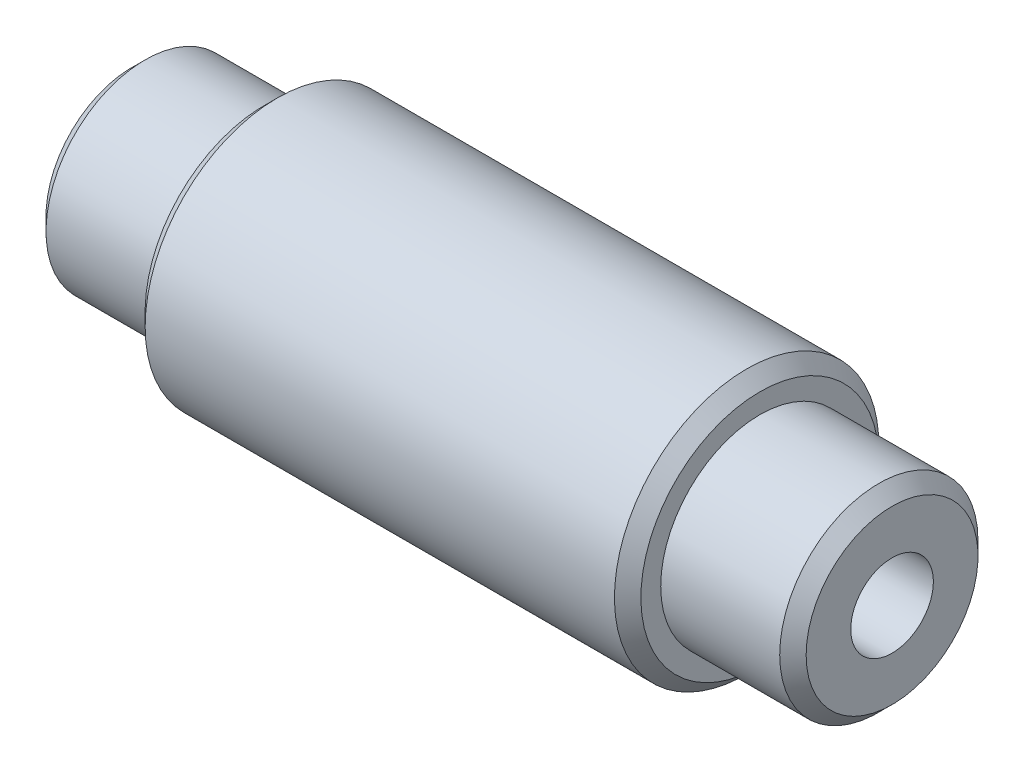
SolidWorks part; units mm, degrees
material "A2017-T4"
ref_plane "Front Plane" through (0, 0, 0) normal (0, 0, 1) x (1, 0, 0)
ref_plane "Top Plane" through (0, 0, 0) normal (0, 1, 0) x (1, 0, 0)
ref_plane "Right Plane" through (0, 0, 0) normal (1, 0, 0) x (0, 0, -1)
sketch "Sketch1" plane through (0, 0, 0) normal (0, 0, 1) x (1, 0, 0)
  line L0 (15, 0) -> (0, 0) construction
  line L3 (0, 0) -> (0, 4)
  line L4 (0, 4) -> (15, 4)
  line L5 (15, 4) -> (15, 0)
  line L8 (0, 0) -> (15, 0)
  dimension "D" = 8
  dimension "L" = 15
revolve "Revolve1" add sketch "Sketch1" angle 360 about L0
chamfer "Chamfer1" distance 0.4 angle 45 2 edges at (0, 4, 0) (15, 4, 0)
ref_plane "Dim. SC" through (6, 0, 0) normal (1, 0, 0) x (0, 0, -1)
ref_plane "Plane1" through (-4, 0, 0) normal (1, 0, 0) x (0, 0, -1)
ref_plane "Plane2" through (19, 0, 0) normal (1, 0, 0) x (0, 0, -1)
sketch "Sketch2" plane through (0, 0, 0) normal (0, 0, 1) x (1, 0, 0)
  line L0 (-4, 0) -> (19, 0) construction
  line L1 (-4, 0) -> (-4, 3)
  line L2 (15, 3) -> (15, 0) construction
  line L3 (0, 0) -> (0, 4) construction
  line L4 (-4, 3) -> (-4, 0) construction
  line L5 (19, 3) -> (19, 0) construction
  line L6 (-4, 3) -> (19, 3)
  line L7 (19, 3) -> (19, 0)
  line L8 (-4, 0) -> (19, 0)
  line L12 (-4, -5.5) -> (-4, 5.5) construction
  line L13 (19, -5.5) -> (19, 5.5) construction
  dimension "P" = 6
  dimension "E" = 4
  dimension "L" = 15
  dimension "F" = 4
  dimension "V" = 6
revolve "Revolve2" add sketch "Sketch2" angle 360 about L0
hole_wizard "Tapped Hole1" positions "Sketch4" profile "Sketch3" tap size "M4x0.7" standard "JIS"
sketch "Sketch4" plane through (-4, 0, 0) normal (1, 0, 0) x (0, 0, -1)
  point P0 (0, 0)
sketch "Sketch3" plane through (-4, 0, 0) normal (0, 1, 0) x (0, 0, 1)
  line L0 (0, 0) -> (0, 9.2511)
  line L1 (0, 9.2511) -> (1.25, 8.5)
  line L2 (1.25, 8.5) -> (1.25, 0)
  line L3 (1.5, 8.5) -> (1.5, 0) construction
  line L5 (1.25, 0) -> (0, 0)
  line L10 (0, 9.2511) -> (-1.25, 8.5) construction
  line L11 (0, 0) -> (0, 9.2511) construction
  dimension "Tap Drill Dia." = 2.5
  dimension "Tap Drill Depth" = 8.5
  dimension "Drill Angle" = 118
  dimension "Pilot hole Tip" = 9.2511
  dimension "M" = 3
cosmetic thread "Hole Thread1" parameters "Mx2"=6, "M"=3
hole_wizard "Tapped Hole2" positions "Sketch6" profile "Sketch5" tap size "M4x0.7" standard "JIS"
sketch "Sketch6" plane through (19, 1.8547, 0.4609) normal (1, 0, 0) x (0, 0, -1)
  point P0 (0.4609, -1.8547)
sketch "Sketch5" plane through (19, 0, 0) normal (0, 1, 0) x (0, 0, -1)
  line L0 (0, 0) -> (0, 9.2511)
  line L1 (0, 9.2511) -> (1.25, 8.5)
  line L2 (1.25, 8.5) -> (1.25, 0)
  line L3 (1.5, 8.5) -> (1.5, 0) construction
  line L5 (1.25, 0) -> (0, 0)
  line L10 (0, 9.2511) -> (-1.25, 8.5) construction
  line L11 (0, 0) -> (0, 9.2511) construction
  dimension "Tap Drill Dia." = 2.5
  dimension "Tap Drill Depth" = 8.5
  dimension "Drill Angle" = 118
  dimension "Pilot hole Tip" = 9.2511
  dimension "N" = 3
cosmetic thread "Hole Thread2" parameters "Nx2"=6, "N"=3
sketch "Sketch7" plane through (-4, 0, 0) normal (1, 0, 0) x (0, 0, -1)
  circle A0 centre (0, 0) radius 1.25
  circle A1 centre (0, 0) radius 1.25
  dimension "D1" = 2.5
  dimension "D2" = 2.5
extrude "Boss-Extrude1" [suppressed] add sketch "Sketch7" along normal blind 6
sketch "Sketch8" plane through (19, 0, 0) normal (1, 0, 0) x (0, 0, -1)
  circle A0 centre (0, 0) radius 1.25
  circle A1 centre (0, 0) radius 1.25
  dimension "D1" = 2.5
  dimension "D2" = 2.5
extrude "Boss-Extrude2" [suppressed] add sketch "Sketch8" against normal blind 6
chamfer "Chamfer2" distance 0.4 angle 45 1 edges at (-4, 0, 3)
chamfer "Chamfer3" distance 0.4 angle 45 1 edges at (19, 0, 3)
ref_plane "Plane3" [suppressed] through (-2, 0, 0) normal (1, 0, 0) x (0, 0, -1)
ref_plane "Plane4" [suppressed] through (27, 0, 0) normal (1, 0, 0) x (0, 0, -1)
sketch "Sketch9" [suppressed] plane through (0, 0, 0) normal (0, 0, 1) x (1, 0, 0)
  line L0 (-2, 0) -> (27, 0) construction
  line L1 (-2, 0) -> (-2, 4) construction
  line L2 (0, 4.6) -> (0, -4.6) construction
  line L4 (-2, 4) -> (-2, 0)
  line L5 (27, 4) -> (27, 0)
  line L6 (-2, 4) -> (27, 4)
  line L7 (27, 4) -> (27, 0) construction
  line L8 (-2, 0) -> (27, 0)
  line L9 (-2, -5.5) -> (-2, 5.5) construction
  line L10 (27, -5.5) -> (27, 5.5) construction
  line L11 (25, 4) -> (25, 0) construction
  line L12 (0, 0) -> (0, 5) construction
  dimension "P" = 6
  dimension "L" = 15
  dimension "V" = 8
  dimension "H" = 2
  dimension "G" = 2
revolve "Revolve3" [suppressed] add sketch "Sketch9" angle 360 about L0
hole_wizard "Tapped Hole3" [suppressed] positions "Sketch11" profile "Sketch10" tap size "M4x0.7" standard "JIS"
sketch "Sketch11" [suppressed] plane through (-2, 0, 0) normal (1, 0, 0) x (0, 0, -1)
  point P0 (0, 0)
sketch "Sketch10" [suppressed] plane through (-2, 0, 0) normal (0, 1, 0) x (0, 0, 1)
  line L0 (0, 0) -> (0, 12.4914)
  line L1 (0, 12.4914) -> (1.65, 11.5)
  line L2 (1.65, 11.5) -> (1.65, 0)
  line L3 (2, 11.5) -> (2, 0) construction
  line L5 (1.65, 0) -> (0, 0)
  line L10 (0, 12.4914) -> (-1.65, 11.5) construction
  line L11 (0, 0) -> (0, 12.4914) construction
  dimension "Tap Drill Dia." = 3.3
  dimension "Tap Drill Depth" = 11.5
  dimension "Drill Angle" = 118
  dimension "Pilot hole Tip" = 12.4914
  dimension "M" = 3
cosmetic thread "Hole Thread3" [suppressed] parameters "Mx2"=8, "M"=3
hole_wizard "Tapped Hole4" [suppressed] positions "Sketch13" profile "Sketch12" tap size "M5x0.8" standard "JIS"
sketch "Sketch13" [suppressed] plane through (27, 0, 0) normal (1, 0, 0) x (0, 0, -1)
  point P0 (0, 0)
sketch "Sketch12" [suppressed] plane through (27, 0, 0) normal (0, 1, 0) x (0, 0, -1)
  line L0 (0, 0) -> (0, 15.2618)
  line L1 (0, 15.2618) -> (2.1, 14)
  line L2 (2.1, 14) -> (2.1, 0)
  line L3 (2, 14) -> (2, 0) construction
  line L5 (2.1, 0) -> (0, 0)
  line L10 (0, 15.2618) -> (-2.1, 14) construction
  line L11 (0, 0) -> (0, 15.2618) construction
  dimension "Tap Drill Dia." = 4.2
  dimension "Tap Drill Depth" = 14
  dimension "Drill Angle" = 118
  dimension "Pilot hole Tip" = 15.2618
  dimension "N" = 3
cosmetic thread "Hole Thread4" [suppressed] parameters "Nx2"=10, "N"=3
sketch "Sketch14" [suppressed] plane through (-2, 0, 0) normal (1, 0, 0) x (0, 0, -1)
  circle A0 centre (0, 0) radius 2.1
  circle A1 centre (0, 0) radius 1.65
  dimension "D1" = 3.3
  dimension "D2" = 4.2
extrude "Boss-Extrude3" [suppressed] add sketch "Sketch14" along normal blind 6
sketch "Sketch15" [suppressed] plane through (27, 0, 0) normal (1, 0, 0) x (0, 0, -1)
  circle A0 centre (0, 0) radius 2.1
  circle A1 centre (0, 0) radius 1.65
  dimension "D1" = 4.2
  dimension "D2" = 3.3
extrude "Boss-Extrude4" [suppressed] add sketch "Sketch15" against normal blind 6
chamfer "Chamfer4" [suppressed] distance 0.4 angle 45
chamfer "Chamfer5" [suppressed] distance 0.4 angle 45
sketch "Sketch16" [suppressed] plane through (0, 0, 0) normal (0, 1, 0) x (1, 0, 0)
  line L0 (6, 5) -> (14, 5)
  line L1 (6, 5) -> (6, 4)
  line L2 (6, 4) -> (14, 4)
  line L3 (14, 5) -> (14, 4)
  line L4 (6, -5) -> (14, -5)
  line L5 (6, -5) -> (6, -4)
  line L6 (6, -4) -> (14, -4)
  line L7 (14, -5) -> (14, -4)
  line L8 (0, 0) -> (25, 0) construction
  line L9 (6, -5.5) -> (6, 5.5) construction
  line L10 (0, 0) -> (25, 0) construction
  line L11 (10, 5) -> (10, 4) construction
  dimension "W" = 8
  dimension "L1_s" = 8
  dimension "D" = 8
  dimension "L1_s_L" = 8
extrude "Cut-Extrude1" [suppressed] cut sketch "Sketch16" against normal through all and the other way through all
ref_plane "Pilot & Wrench Flats Configurable_SEC" [suppressed] through (10, 0, 0) normal (1, 0, 0) x (0, 0, -1)
hole_wizard "Tapped Hole5" [suppressed] positions "Sketch18" profile "Sketch17" tap size "M4x0.7" standard "JIS"
sketch "Sketch18" [suppressed] plane through (-5, 0, 0) normal (1, 0, 0) x (0, 0, -1)
  point P0 (0, 0)
sketch "Sketch17" [suppressed] plane through (-5, 0, 0) normal (0, 1, 0) x (0, 0, 1)
  line L0 (0, 0) -> (0, 16.4914)
  line L1 (0, 16.4914) -> (1.65, 15.5)
  line L2 (1.65, 15.5) -> (1.65, 0)
  line L5 (1.65, 0) -> (0, 0)
  line L10 (0, 16.4914) -> (-1.65, 15.5) construction
  line L11 (0, 0) -> (0, 16.4914) construction
  dimension "Tap Drill Dia." = 3.3
  dimension "Tap Drill Depth" = 15.5
  dimension "Drill Angle" = 118
cosmetic thread "Hole Thread5" [suppressed] parameters "Mx3"=12, "MD"=4
hole_wizard "Tapped Hole6" [suppressed] positions "Sketch20" profile "Sketch19" tap size "M4x0.7" standard "JIS"
sketch "Sketch20" [suppressed] plane through (-2, 0, 0) normal (1, 0, 0) x (0, 0, -1)
  point P0 (0, 0)
sketch "Sketch19" [suppressed] plane through (-2, 0, 0) normal (0, 1, 0) x (0, 0, 1)
  line L0 (0, 0) -> (0, 16.4914)
  line L1 (0, 16.4914) -> (1.65, 15.5)
  line L2 (1.65, 15.5) -> (1.65, 0)
  line L5 (1.65, 0) -> (0, 0)
  line L10 (0, 16.4914) -> (-1.65, 15.5) construction
  line L11 (0, 0) -> (0, 16.4914) construction
  dimension "Tap Drill Dia." = 3.3
  dimension "Tap Drill Depth" = 15.5
  dimension "Drill Angle" = 118
cosmetic thread "Hole Thread6" [suppressed] parameters "Mx3"=12, "MD"=4
hole_wizard "Tapped Hole7" [suppressed] positions "Sketch22" profile "Sketch21" tap size "M4x0.7" standard "JIS"
sketch "Sketch22" [suppressed] plane through (30, 0, 0) normal (1, 0, 0) x (0, 0, -1)
  point P0 (0, 0)
sketch "Sketch21" [suppressed] plane through (30, 0, 0) normal (0, 1, 0) x (0, 0, -1)
  line L0 (0, 0) -> (0, 16.4914)
  line L1 (0, 16.4914) -> (1.65, 15.5)
  line L2 (1.65, 15.5) -> (1.65, 0)
  line L5 (1.65, 0) -> (0, 0)
  line L10 (0, 16.4914) -> (-1.65, 15.5) construction
  line L11 (0, 0) -> (0, 16.4914) construction
  dimension "Tap Drill Dia." = 3.3
  dimension "Tap Drill Depth" = 15.5
  dimension "Drill Angle" = 118
cosmetic thread "Hole Thread7" [suppressed] parameters "Nx3"=12, "ND"=4
hole_wizard "Tapped Hole8" [suppressed] positions "Sketch24" profile "Sketch23" tap size "M4x0.7" standard "JIS"
sketch "Sketch24" [suppressed] plane through (27, 0, 0) normal (1, 0, 0) x (0, 0, -1)
  point P0 (0, 0)
sketch "Sketch23" [suppressed] plane through (27, 0, 0) normal (0, 1, 0) x (0, 0, -1)
  line L0 (0, 0) -> (0, 16.4914)
  line L1 (0, 16.4914) -> (1.65, 15.5)
  line L2 (1.65, 15.5) -> (1.65, 0)
  line L5 (1.65, 0) -> (0, 0)
  line L10 (0, 16.4914) -> (-1.65, 15.5) construction
  line L11 (0, 0) -> (0, 16.4914) construction
  dimension "Tap Drill Dia." = 3.3
  dimension "Tap Drill Depth" = 15.5
  dimension "Drill Angle" = 118
cosmetic thread "Hole Thread8" [suppressed] parameters "Nx3"=12, "ND"=4
sketch "Sketch25" [suppressed] plane through (0, 0, 0) normal (0, 1, 0) x (1, 0, 0)
  line L0 (0, 0) -> (25, 0) construction
  line L1 (10, 5) -> (10, 4) construction
  line L3 (6, 5) -> (14, 5)
  line L4 (6, 5) -> (6, 4)
  line L5 (6, 4) -> (14, 4)
  line L6 (14, 5) -> (14, 4)
  line L7 (6, -5) -> (14, -5)
  line L8 (6, -5) -> (6, -4)
  line L9 (6, -4) -> (14, -4)
  line L10 (14, -5) -> (14, -4)
  line L11 (6, -5.5) -> (6, 5.5) construction
  dimension "W" = 8
  dimension "L1_s" = 8
  dimension "D" = 8
  dimension "L1_s_L" = 8
extrude "Cut-Extrude2" [suppressed] cut sketch "Sketch25" against normal through all and the other way through all
ref_plane "SC_SEC" [suppressed] through (10, 0, 0) normal (1, 0, 0) x (0, 0, -1)
sketch "Sketch26" [suppressed] plane through (0, 0, 0) normal (-1, 0, 0) x (0, 0, 1)
  circle A0 centre (0, 0) radius 3.5
  circle A1 centre (0, 0) radius 4
  dimension "P" = 6
  dimension "PKH" = 7
extrude "Cut-Extrude3" [suppressed] cut sketch "Sketch26" along normal through all
chamfer "Chamfer6" [suppressed] distance 0.4 angle 45
chamfer "Chamfer7" [suppressed] distance 0.4 angle 45
sketch "Sketch27" [suppressed] plane through (25, 0, 0) normal (1, 0, 0) x (0, 0, -1)
  circle A0 centre (0, 0) radius 3.5
  circle A1 centre (0, 0) radius 4
  dimension "V" = 6
  dimension "VKH" = 7
extrude "Cut-Extrude4" [suppressed] cut sketch "Sketch27" along normal through all
chamfer "Chamfer8" [suppressed] distance 0.4 angle 45
chamfer "Chamfer9" [suppressed] distance 0.4 angle 45
ref_plane "Plane5" [suppressed] through (0, 5, 0) normal (0, 1, 0) x (1, 0, 0)
hole_wizard "Diameter Hole1" [suppressed] positions "Sketch29" profile "Sketch28" hole size "Ø3.0" standard "JIS"
sketch "Sketch29" [suppressed] plane through (0, 5, 0) normal (0, 1, 0) x (1, 0, 0)
  line L1 (0, 0) -> (7, 0) construction
  point P0 (7, 0)
  dimension "HL" = 7
sketch "Sketch28" [suppressed] plane through (7, 5, 0) normal (1, 0, 0) x (0, 0, 1)
  line L0 (0, 0) -> (0, 10)
  line L1 (0, 10) -> (1.5, 10)
  line L2 (1.5, 10) -> (1.5, 0)
  line L5 (1.5, 0) -> (0, 0)
  line L11 (0, 0) -> (0, 10) construction
  dimension "D_s" = 3
  dimension "Thru Hole Depth" = 10
equation "\"Plane dim\"= \"D@Sketch1\" * 0.5"
equation "\"D1@Sketch7\"=\"Tap Drill Dia.@Sketch3\""
equation "\"D2@Sketch7\"=\"Tap Drill Dia.@Sketch5\""
equation "\"D1@Boss-Extrude1\"=\"M@Sketch3\"*2"
equation "\"D1@Sketch8\"=\"Tap Drill Dia.@Sketch5\""
equation "\"D2@Sketch8\"=\"Tap Drill Dia.@Sketch3\""
equation "\"D1@Boss-Extrude2\"=\"N@Sketch5\"*2"
equation "\"D1@Sketch14\"=\"Tap Drill Dia.@Sketch10\""
equation "\"D2@Sketch14\"=\"Tap Drill Dia.@Sketch12\""
equation "\"D1@Boss-Extrude3\"=\"M@Sketch10\"*2"
equation "\"D1@Sketch15\"=\"Tap Drill Dia.@Sketch12\""
equation "\"D2@Sketch15\"=\"Tap Drill Dia.@Sketch10\""
equation "\"D1@Boss-Extrude4\"=\"N@Sketch12\"*2"
equation "\"MSM_1\"=0"
equation "\"MSM_2\"=0"
equation "\"MSM_3\"= 0"
equation "\"MSM_4\"= 0"
equation "\"Position M@Plane1\"=iif(\"MSM_1\"=1,0,\"E@Sketch2\")"
equation "\"Position N@Plane2\"=iif(\"MSM_2\"=1,\"L@Sketch1\",\"L@Sketch1\"+\"F@Sketch2\")"
equation "\"Position N@Plane4\"=iif(\"MSM_4\"=1,\"L@Sketch1\",\"L@Sketch1\"+\"H@Sketch9\")"
equation "\"Position M@Plane3\"=iif(\"MSM_3\"=1,0,\"G@Sketch9\")"
